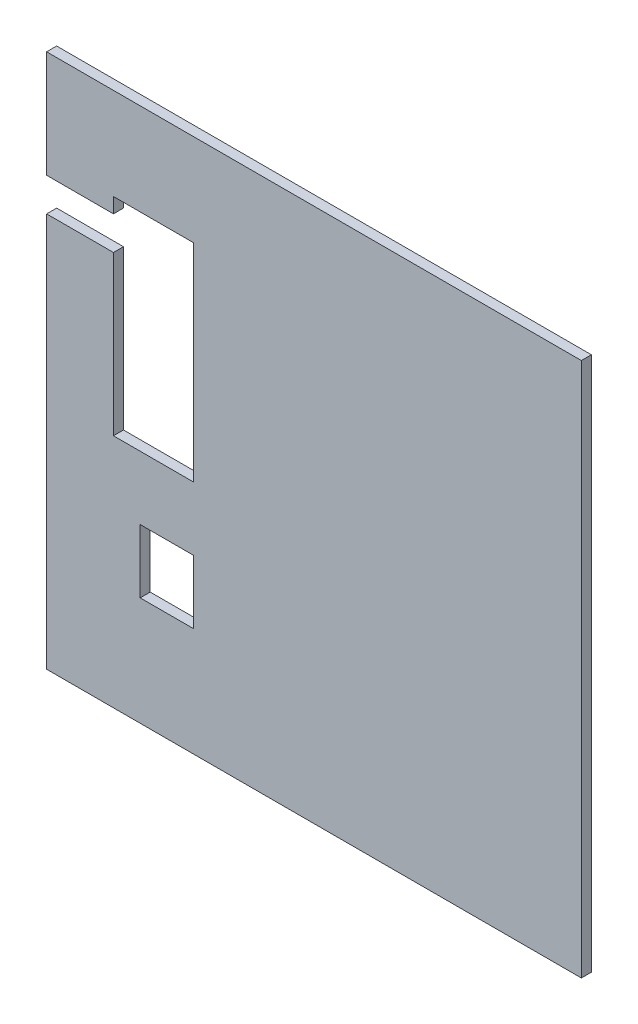
SolidWorks part; units mm, degrees
material "PMMA"
ref_plane "Front Plane" through (0, 0, 0) normal (0, 0, 1) x (1, 0, 0)
ref_plane "Top Plane" through (0, 0, 0) normal (0, 1, 0) x (1, 0, 0)
ref_plane "Right Plane" through (0, 0, 0) normal (1, 0, 0) x (0, 0, -1)
sketch "Sketch1" plane through (0, 0, 0) normal (0, 0, 1) x (1, 0, 0)
  line L0 (-36, -9.5) -> (-60, -9.5)
  line L1 (80, -80) -> (-80, -80)
  line L2 (80, -80) -> (80, 80)
  line L3 (80, 80) -> (-80, 80)
  line L4 (-80, -80) -> (-80, 38)
  line L5 (80, -80) -> (-80, 80) construction
  line L6 (80, 80) -> (-80, -80) construction
  line L8 (-80, 48) -> (-80, 38) construction
  line L10 (-36, 52.5) -> (-36, -9.5)
  line L11 (-60, -9.5) -> (-60, 38)
  line L12 (-60, 38) -> (-80, 38)
  line L13 (-80, 38) -> (-80, 48) construction
  line L14 (-80, 48) -> (-80, 80)
  line L15 (-80, 48) -> (-60, 48)
  line L16 (-60, 48) -> (-60, 52.5)
  line L17 (-60, 52.5) -> (-36, 52.5)
  line L18 (-38, 50.5) -> (-50, 50.5) construction
  line L19 (-38, 35.5) -> (-38, 50.5) construction
  line L20 (-50, -7.5) -> (-38, -7.5) construction
  line L21 (-50, -30.5) -> (-50, -45.5) construction
  line L22 (-52, -28.5) -> (-36, -28.5)
  line L23 (-52, -28.5) -> (-52, -47.5)
  line L24 (-52, -47.5) -> (-36, -47.5)
  line L25 (-36, -28.5) -> (-36, -47.5)
  line L26 (-38, -30.5) -> (-50, -30.5) construction
  line L27 (-50, -45.5) -> (-38, -45.5) construction
  line L28 (-38, -45.5) -> (-38, -30.5) construction
  point P0 (0, 0)
  point P11 (-80, 43)
  dimension "D1" = 160
  dimension "D2" = 20
  dimension "D3" = 10
  dimension "D4" = 37
  dimension "D5" = 2
  dimension "D6" = 2
  dimension "D7" = 2
  dimension "D8" = 2
  dimension "D9" = 2
  dimension "D10" = 2
  dimension "D11" = 2
extrude "Boss-Extrude1" add sketch "Sketch1" along normal blind 3
